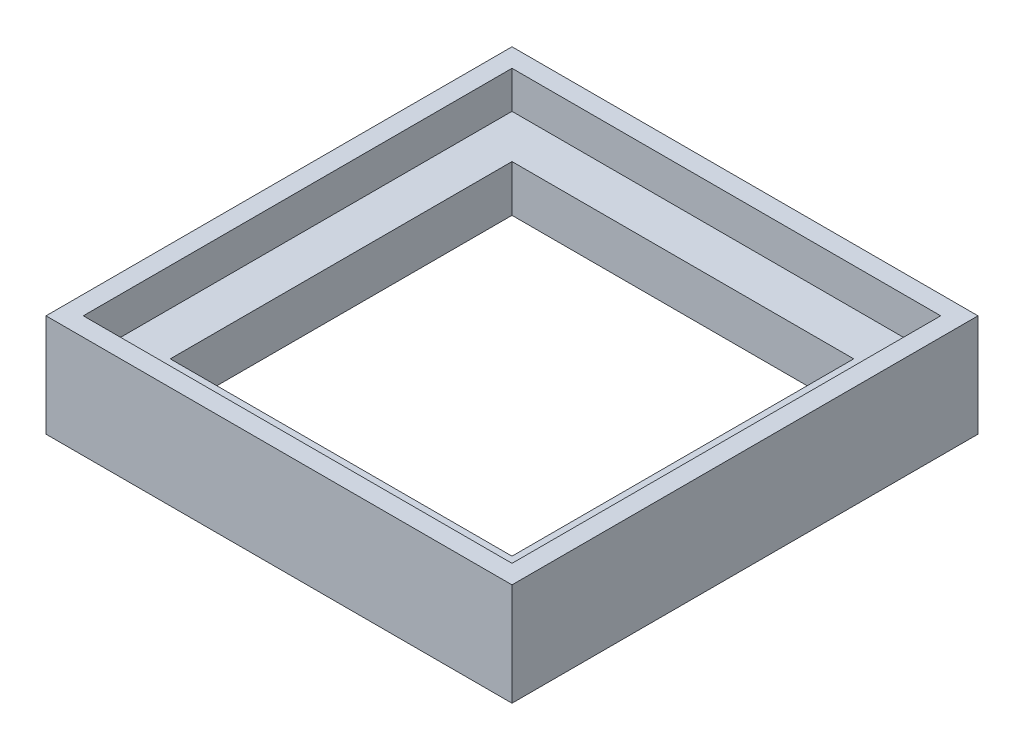
SolidWorks part; units mm, degrees
ref_plane "Спереди" through (0, 0, 0) normal (0, 0, 1) x (1, 0, 0)
ref_plane "Сверху" through (0, 0, 0) normal (0, 1, 0) x (1, 0, 0)
ref_plane "Справа" through (0, 0, 0) normal (1, 0, 0) x (0, 0, -1)
sketch "Эскиз1" plane through (0, 0, 0) normal (0, 1, 0) x (1, 0, 0)
  line L1 (-75, -75) -> (75, -75)
  line L2 (-75, -75) -> (-75, 75)
  line L3 (-75, 75) -> (75, 75)
  line L4 (75, -75) -> (75, 75)
  line L5 (-75, -75) -> (75, 75) construction
  line L6 (-75, 75) -> (75, -75) construction
  point P0 (0, 0)
extrude "Бобышка-Вытянуть1" add sketch "Эскиз1" along normal blind 33
sketch "Эскиз2" plane through (0, 33, 0) normal (0, 1, 0) x (1, 0, 0)
  line L1 (-69, -69) -> (69, -69)
  line L2 (-69, -69) -> (-69, 69)
  line L3 (-69, 69) -> (69, 69)
  line L4 (69, -69) -> (69, 69)
  line L5 (-69, -69) -> (69, 69) construction
  line L6 (-69, 69) -> (69, -69) construction
  point P0 (0, 0)
extrude "Вырез-Вытянуть1" cut sketch "Эскиз2" against normal blind 12
sketch "Эскиз3" plane through (0, 0, 0) normal (0, -1, 0) x (-1, 0, 0)
  line L1 (65, 65) -> (-65, 65)
  line L2 (65, 65) -> (65, -65)
  line L3 (65, -65) -> (-65, -65)
  line L4 (-65, 65) -> (-65, -65)
  line L5 (65, 65) -> (-65, -65) construction
  line L6 (65, -65) -> (-65, 65) construction
  point P0 (0, 0)
extrude "Вырез-Вытянуть2" cut sketch "Эскиз3" against normal blind 6
sketch "Эскиз4" plane through (0, 21, 0) normal (0, 1, 0) x (1, 0, 0)
  line L1 (-55, -55) -> (55, -55)
  line L2 (-55, -55) -> (-55, 55)
  line L3 (-55, 55) -> (55, 55)
  line L4 (55, -55) -> (55, 55)
  line L5 (-55, -55) -> (55, 55) construction
  line L6 (-55, 55) -> (55, -55) construction
  point P0 (0, 0)
extrude "Вырез-Вытянуть3" cut sketch "Эскиз4" against normal through all
